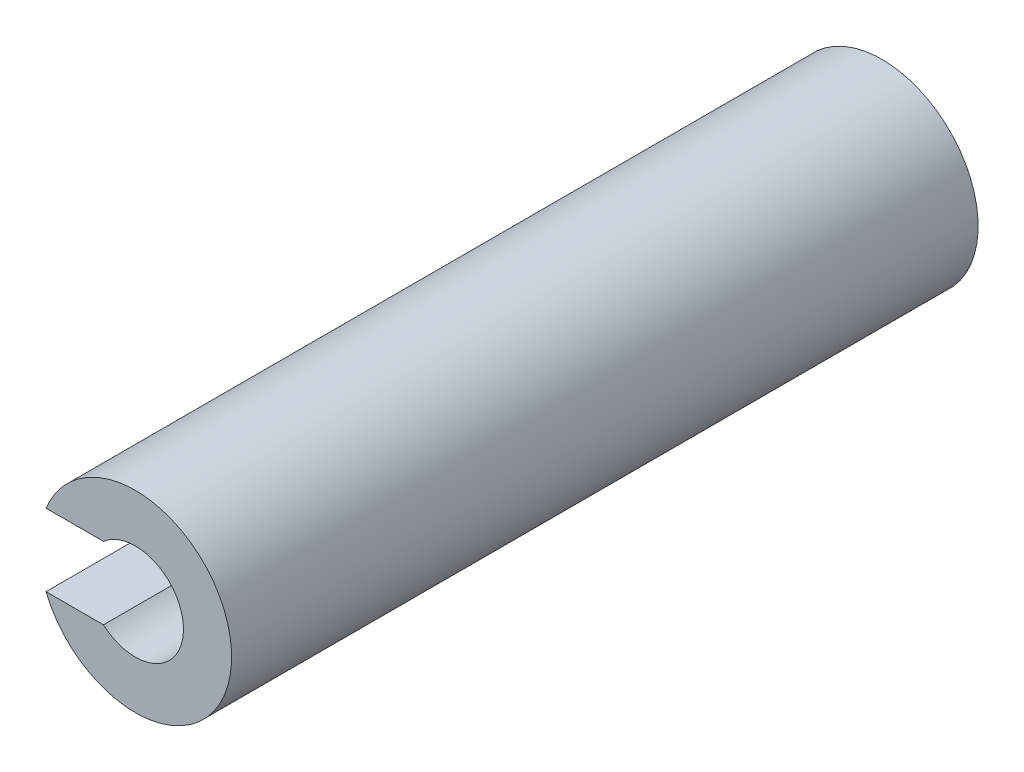
SolidWorks part; units mm, degrees
material "Brass"
ref_plane "Front Plane" through (0, 0, 0) normal (0, 0, 1) x (1, 0, 0)
ref_plane "Top Plane" through (0, 0, 0) normal (0, 1, 0) x (1, 0, 0)
ref_plane "Right Plane" through (0, 0, 0) normal (1, 0, 0) x (0, 0, -1)
sketch "Sketch1" plane through (0, 0, -64.8963) normal (0, 0, 1) x (1, 0, 0)
  line L0 (0, -28) -> (0, -10.6446) construction
  line L7 (0, -10.6446) -> (-2, -10.6446) construction
  line L16 (-2, -10.6446) -> (-2, -9.1446) construction
  line L17 (-3.7081, -12.1446) -> (-1.3229, -12.1446)
  line L23 (-2, -9.1446) -> (-3.7081, -9.1446)
  line L25 (-2, -9.1446) -> (-1.3229, -9.1446)
  line L26 (0, -10.6446) -> (-1.3229, -9.1446) construction
  line L28 (-2, -10.6446) -> (-2, -12.1446) construction
  arc A1 (-3.7081, -12.1446) -> (-3.7081, -9.1446) centre (0, -10.6446) ccw
  arc A3 (-1.3229, -12.1446) -> (-1.3229, -9.1446) centre (0, -10.6446) ccw
  dimension "D1" = 4
  dimension "D3" = 1.5
  dimension "D2" = 2
extrude "Boss-Extrude1" add sketch "Sketch1" against normal offset from surface 3 and the other way blind 5
sketch "Sketch2" plane through (0, 0, -59.8963) normal (0, 0, 1) x (1, 0, 0)
  line L0 (0, 4.3554) -> (0, -25.6446) construction
  line L1 (0, -10.6446) -> (-2, -10.6446) construction
  line L2 (-2, -10.6446) -> (-4, -10.6446) construction
  line L3 (0, -10.6446) -> (4, -10.6446) construction
  circle A0 centre (0, -10.6446) radius 2 construction
  circle A1 centre (0, -10.6446) radius 4 construction
  arc A2 (-1.3229, -12.1446) -> (-1.3229, -9.1446) centre (0, -10.6446) ccw construction
  arc A3 (-3.7081, -12.1446) -> (-3.7081, -9.1446) centre (0, -10.6446) ccw construction
sketch "Sketch3" plane through (0, 0, 0) normal (1, 0, 0) x (0, 0, -1)
  line L0 (90.8963, -10.6446) -> (64.8963, -10.6446) construction
  line L1 (90.8963, -14.6446) -> (90.8963, -6.6446) construction
  line L3 (64.8963, 0.3554) -> (64.8963, -21.6446) construction
  line L5 (64.8963, -10.6446) -> (59.8963, -10.6446) construction
